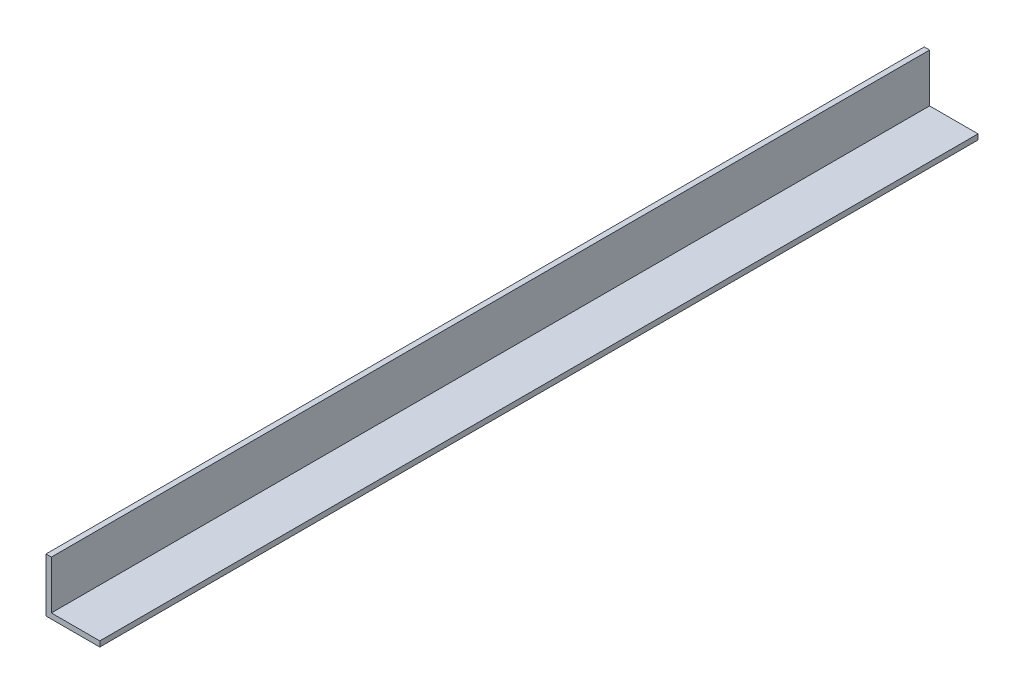
SolidWorks part; units mm, degrees
ref_plane "Спереди" through (0, 0, 0) normal (0, 0, 1) x (1, 0, 0)
ref_plane "Сверху" through (0, 0, 0) normal (0, 1, 0) x (1, 0, 0)
ref_plane "Справа" through (0, 0, 0) normal (1, 0, 0) x (0, 0, -1)
sketch "Эскиз1" plane through (0, 0, 0) normal (0, 0, 1) x (1, 0, 0)
  line L0 (0, 0) -> (0, 30)
  line L1 (0, 30) -> (3, 30)
  line L2 (3, 30) -> (3, 3)
  line L3 (3, 3) -> (30, 3)
  line L4 (30, 3) -> (30, 0)
  line L5 (30, 0) -> (0, 0)
  dimension "D1" = 3
  dimension "D2" = 30
  dimension "D3" = 30
extrude "Бобышка-Вытянуть1" add sketch "Эскиз1" along normal blind 490
